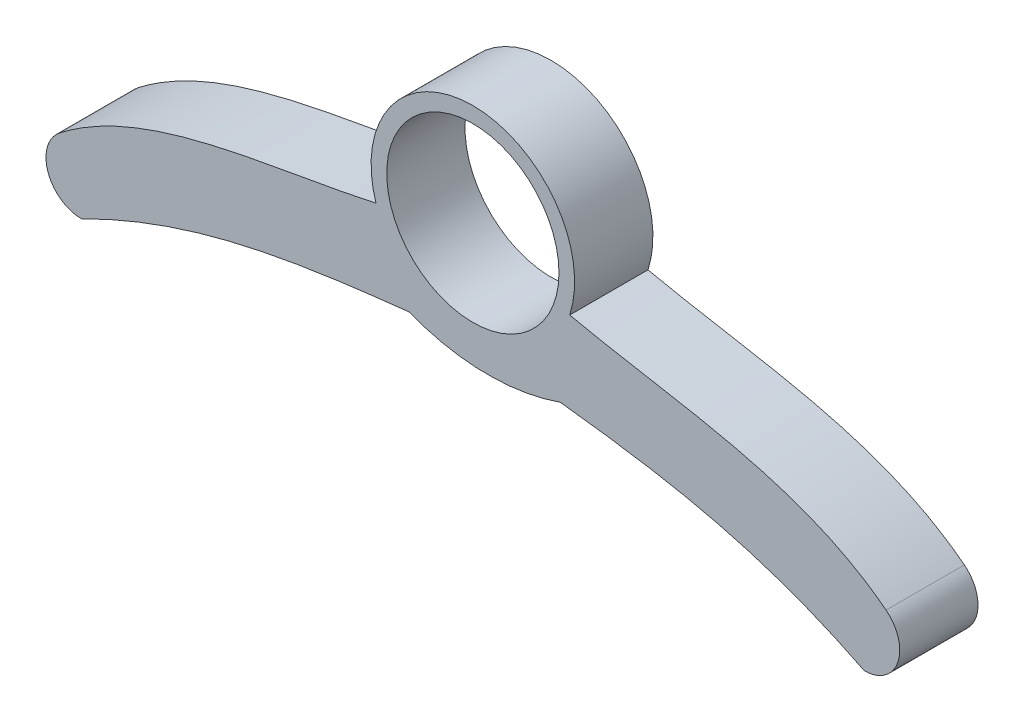
SolidWorks part; units mm, degrees
ref_plane "Front Plane" through (0, 0, 0) normal (0, 0, 1) x (1, 0, 0)
ref_plane "Top Plane" through (0, 0, 0) normal (0, 1, 0) x (1, 0, 0)
ref_plane "Right Plane" through (0, 0, 0) normal (1, 0, 0) x (0, 0, -1)
sketch "Sketch1" plane through (0, 0, 0) normal (0, 0, 1) x (1, 0, 0)
  line L0 (-50, 0) -> (0, 0)
  line L5 (50, 20) -> (-50, 20) construction
  line L6 (50, 20) -> (50, -20) construction
  line L7 (50, -20) -> (-50, -20) construction
  line L8 (-50, 20) -> (-50, -20) construction
  line L9 (50, 20) -> (-50, -20) construction
  line L10 (50, -20) -> (-50, 20) construction
  line L11 (0, -13) -> (0, -6.6081) construction
  circle A4 centre (0, 0) radius 11
  circle A5 centre (0, 0) radius 13
  circle A6 centre (-50, -20) radius 4.5288
  circle A7 centre (50, -20) radius 4.5288
  arc A8 (-8.169, -13.9077) -> (11.1592, -14.2473) centre (1.9529, 11.9762) ccw
  spline S0 degree 3 poles (0, 0) (-15.4924, -7.3727) (-38.0868, -4.98) (-52.783, -16.4272) knots 0 0 0 0 1 1 1 1
  spline S1 degree 3 poles (-50, -24.5288) (-33.0716, -16.0074) (-18.4569, -15.1065) (0, -13) knots 0 0 0 0 1 1 1 1
  spline S2 degree 3 poles (0, 0) (15.4924, -7.3727) (38.0868, -4.98) (52.783, -16.4272) knots 0 0 0 0 1 1 1 1
  spline S3 degree 3 poles (50, -24.5288) (33.0716, -16.0074) (18.4569, -15.1065) (0, -13) knots 0 0 0 0 1 1 1 1
  point P26 (0.0916, 0.0366)
  dimension "D1" = 22
  dimension "D2" = 2
  dimension "D5" = 50
  dimension "D3" = 100
  dimension "D4" = 20
extrude "Boss-Extrude2" add sketch "Sketch1" along normal blind 10 contours A6 S1 | A6 S1 A5 S0 | S0 A4 L0 A5 | A4 S2 A5 L0 | S2 A4 S0 A5 | A8 S3 S1 | S3 A7 S2 A5 | S3 A7
